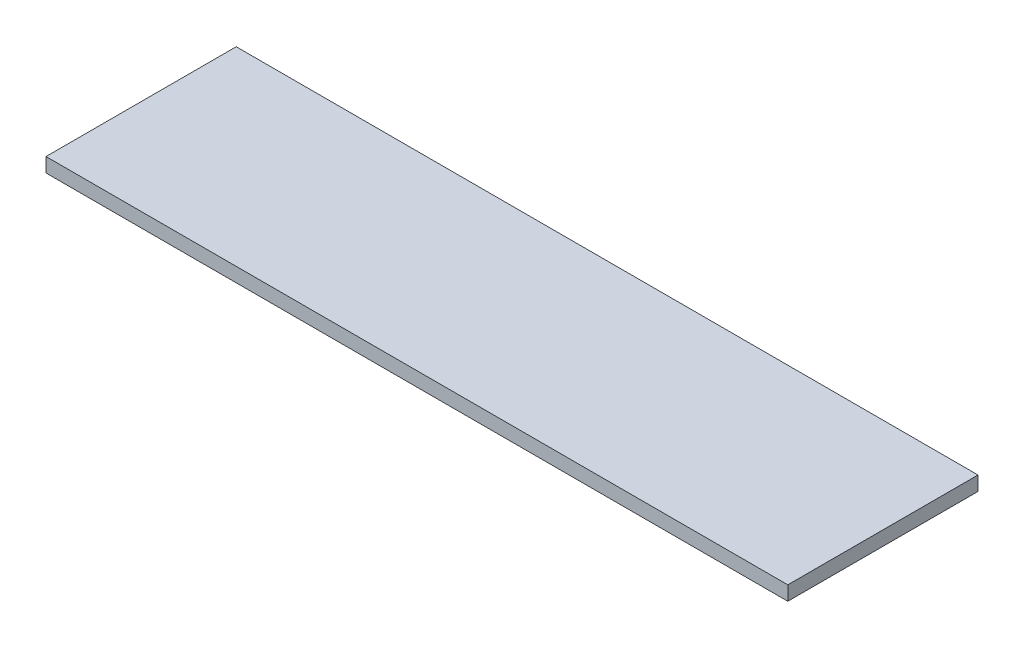
SolidWorks part; units mm, degrees
material "Pine"
ref_plane "Front Plane" through (0, 0, 0) normal (0, 0, 1) x (1, 0, 0)
ref_plane "Top Plane" through (0, 0, 0) normal (0, 1, 0) x (1, 0, 0)
ref_plane "Right Plane" through (0, 0, 0) normal (1, 0, 0) x (0, 0, -1)
sketch "Sketch1" plane through (0, 0, 0) normal (0, 1, 0) x (1, 0, 0)
  line L1 (0, 0) -> (990.6, 0)
  line L2 (0, 0) -> (0, -254)
  line L3 (0, -254) -> (990.6, -254)
  line L4 (990.6, 0) -> (990.6, -254)
  dimension "D1" = 254
  dimension "D2" = 990.6
extrude "Boss-Extrude1" add sketch "Sketch1" along normal blind 19.05
